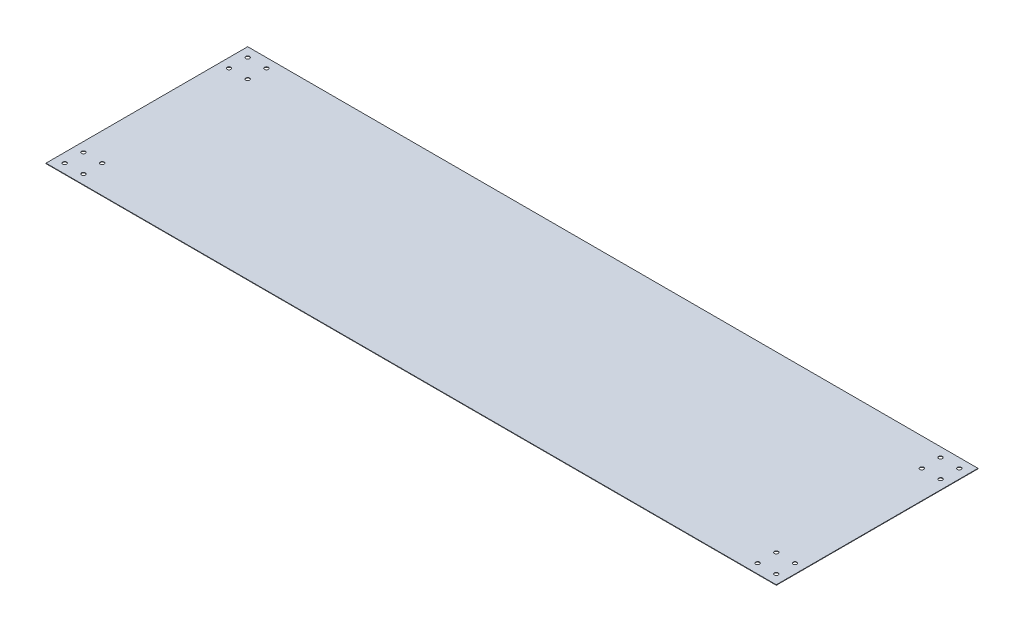
SolidWorks part; units mm, degrees
ref_plane "Front Plane" through (0, 0, 0) normal (0, 0, 1) x (1, 0, 0)
ref_plane "Top Plane" through (0, 0, 0) normal (0, 1, 0) x (1, 0, 0)
ref_plane "Right Plane" through (0, 0, 0) normal (1, 0, 0) x (0, 0, -1)
sketch "Sketch1" plane through (0, 0, 0) normal (0, 1, 0) x (1, 0, 0)
  line L1 (-780.005, 215.425) -> (780.005, 215.425)
  line L2 (-780.005, 215.425) -> (-780.005, -215.425)
  line L3 (-780.005, -215.425) -> (780.005, -215.425)
  line L4 (780.005, 215.425) -> (780.005, -215.425)
  line L5 (-780.005, 215.425) -> (780.005, -215.425) construction
  line L6 (-780.005, -215.425) -> (780.005, 215.425) construction
  line L7 (-740.005, 175.425) -> (740.005, 175.425) construction
  line L8 (-740.005, 175.425) -> (-740.005, -175.425) construction
  line L9 (-740.005, -175.425) -> (740.005, -175.425) construction
  line L10 (740.005, 175.425) -> (740.005, -175.425) construction
  line L11 (-740.005, 175.425) -> (740.005, -175.425) construction
  line L12 (-740.005, -175.425) -> (740.005, 175.425) construction
  line L13 (-760.005, 195.425) -> (-720.005, 195.425) construction
  line L14 (-760.005, 195.425) -> (-760.005, 155.425) construction
  line L15 (-760.005, 155.425) -> (-720.005, 155.425) construction
  line L16 (-720.005, 195.425) -> (-720.005, 155.425) construction
  line L17 (-760.005, 195.425) -> (-720.005, 155.425) construction
  line L18 (-760.005, 155.425) -> (-720.005, 195.425) construction
  line L19 (-760.005, -155.425) -> (-720.005, -155.425) construction
  line L20 (-760.005, -155.425) -> (-760.005, -195.425) construction
  line L21 (-760.005, -195.425) -> (-720.005, -195.425) construction
  line L22 (-720.005, -155.425) -> (-720.005, -195.425) construction
  line L23 (-760.005, -155.425) -> (-720.005, -195.425) construction
  line L24 (-760.005, -195.425) -> (-720.005, -155.425) construction
  line L25 (720.005, -155.425) -> (760.005, -155.425) construction
  line L26 (720.005, -155.425) -> (720.005, -195.425) construction
  line L27 (720.005, -195.425) -> (760.005, -195.425) construction
  line L28 (760.005, -155.425) -> (760.005, -195.425) construction
  line L29 (720.005, -155.425) -> (760.005, -195.425) construction
  line L30 (720.005, -195.425) -> (760.005, -155.425) construction
  line L31 (720.005, 195.425) -> (760.005, 195.425) construction
  line L32 (720.005, 195.425) -> (720.005, 155.425) construction
  line L33 (720.005, 155.425) -> (760.005, 155.425) construction
  line L34 (760.005, 195.425) -> (760.005, 155.425) construction
  line L35 (720.005, 195.425) -> (760.005, 155.425) construction
  line L36 (720.005, 155.425) -> (760.005, 195.425) construction
  line L37 (-780.005, 215.425) -> (-700.005, 215.425) construction
  line L38 (-780.005, 215.425) -> (-780.005, 135.425) construction
  line L39 (-780.005, 135.425) -> (-700.005, 135.425) construction
  line L40 (-700.005, 215.425) -> (-700.005, 135.425) construction
  line L41 (-780.005, 215.425) -> (-700.005, 135.425) construction
  line L42 (-780.005, 135.425) -> (-700.005, 215.425) construction
  line L43 (-760.005, 195.425) -> (760.005, 195.425) construction
  line L44 (-760.005, 195.425) -> (-760.005, -195.425) construction
  line L45 (-760.005, -195.425) -> (760.005, -195.425) construction
  line L46 (760.005, 195.425) -> (760.005, -195.425) construction
  line L47 (-760.005, 195.425) -> (760.005, -195.425) construction
  line L48 (-760.005, -195.425) -> (760.005, 195.425) construction
  circle A0 centre (-760.005, 195.425) radius 4.1
  circle A1 centre (-720.005, 195.425) radius 4.1
  circle A2 centre (-720.005, 155.425) radius 4.1
  circle A3 centre (-760.005, 155.425) radius 4.1
  circle A4 centre (-760.005, -195.425) radius 4.1
  circle A5 centre (-760.005, -155.425) radius 4.1
  circle A6 centre (-720.005, -155.425) radius 4.1
  circle A7 centre (-720.005, -195.425) radius 4.1
  circle A8 centre (720.005, -195.425) radius 4.1
  circle A9 centre (760.005, -195.425) radius 4.1
  circle A10 centre (760.005, -155.425) radius 4.1
  circle A11 centre (720.005, -155.425) radius 4.1
  circle A12 centre (760.005, 155.425) radius 4.1
  circle A13 centre (760.005, 195.425) radius 4.1
  circle A14 centre (720.005, 155.425) radius 4.1
  circle A15 centre (720.005, 195.425) radius 4.1
  point P0 (0, 0)
  point P6 (0, 0)
  point P46 (0, 0)
  point P51 (760.005, 175.425)
  dimension "D3" = 8.2
  dimension "D1" = 40
  dimension "D2" = 80
  dimension "D4" = 20
  dimension "D5" = 20
  dimension "D6" = 1520.01
  dimension "D7" = 390.85
extrude "Boss-Extrude1" add sketch "Sketch1" along normal blind 1
